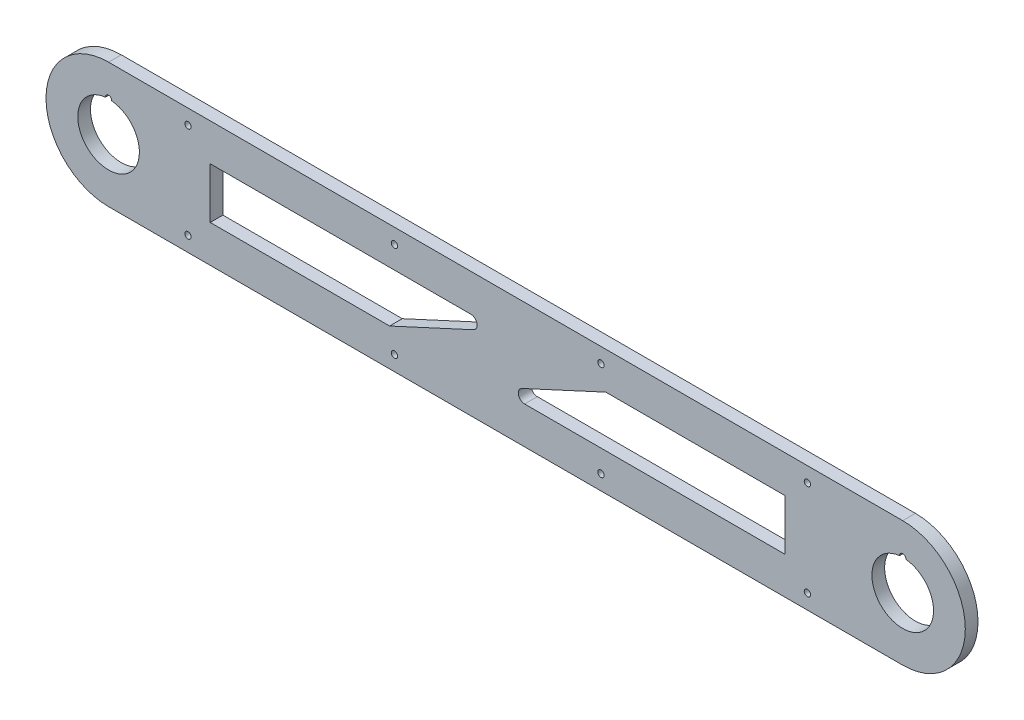
SolidWorks part; units mm, degrees
ref_plane "前视基准面" through (0, 0, 0) normal (0, 0, 1) x (1, 0, 0)
ref_plane "上视基准面" through (0, 0, 0) normal (0, 1, 0) x (1, 0, 0)
ref_plane "右视基准面" through (0, 0, 0) normal (1, 0, 0) x (0, 0, -1)
sketch "草图1" plane through (0, 0, 0) normal (0, 0, 1) x (1, 0, 0)
  line L0 (0, 0) -> (250, 0) construction
  line L1 (0, 0) -> (0, 15.4343) construction
  line L6 (0, 0) -> (0, -15.4343) construction
  line L7 (0, 19.7) -> (250, 19.7)
  line L8 (0, -19.7) -> (250, -19.7)
  line L9 (250, 0) -> (225.3628, 42.6729) construction
  line L10 (240.15, 17.0607) -> (232.3558, 12.5607) construction
  line L11 (0, 19.7) -> (232.3558, 12.5607) construction
  line L12 (240.15, -17.0607) -> (232.3558, -12.5607) construction
  line L13 (0, -19.7) -> (232.3558, -12.5607) construction
  circle A0 centre (0, 0) radius 9.7
  circle A1 centre (250, 0) radius 9.7
  circle A2 centre (0, 0) radius 19.7 construction
  circle A3 centre (250, 0) radius 19.7 construction
  arc A4 (0, 19.7) -> (0, -19.7) centre (0, 0) ccw
  arc A7 (240.15, -17.0607) -> (250, 19.7) centre (250, 0) ccw construction
  arc A8 (250, 19.7) -> (250, -19.7) centre (250, 0) cw
  dimension "D1" = 10
  dimension "D2" = 19.4
  dimension "D3" = 60
extrude "凸台-拉伸1" add sketch "草图1" along normal blind 4
sketch "草图2" plane through (0, 0, 4) normal (0, 0, 1) x (1, 0, 0)
  line L0 (0, 0) -> (250, 0) construction
  line L1 (0, 0) -> (0, -8.921) construction
  circle A0 centre (25, 15) radius 1
  circle A1 centre (90, 15) radius 1
  circle A2 centre (155, 15) radius 1
  circle A3 centre (220, 15) radius 1
  circle A4 centre (90, -15) radius 1
  circle A5 centre (155, -15) radius 1
  circle A6 centre (220, -15) radius 1
  circle A7 centre (25, -15) radius 1
  dimension "D1" = 2
  dimension "D2" = 25
  dimension "D3" = 15
extrude "切除-拉伸1" cut sketch "草图2" against normal blind 10
sketch "草图3" plane through (0, 0, 4) normal (0, 0, 1) x (1, 0, 0)
  line L4 (32, 8) -> (114.0233, 8)
  line L5 (114.8614, 4.1841) -> (88.4625, -8)
  line L6 (88.4625, -8) -> (32, -8)
  line L7 (32, -8) -> (32, 8)
  line L13 (156.5375, 8) -> (130.1386, -4.1841)
  line L14 (213, -8) -> (130.9767, -8)
  line L15 (213, 8) -> (213, -8)
  line L16 (156.5375, 8) -> (213, 8)
  arc A0 (130.9767, -8) -> (130.1386, -4.1841) centre (130.9767, -6) cw
  arc A1 (114.8614, 4.1841) -> (114.0233, 8) centre (114.0233, 6) ccw
  dimension "D1" = 2
extrude "切除-拉伸2" cut sketch "草图3" against normal blind 10
sketch "草图4" plane through (0, 0, 4) normal (0, 0, 1) x (1, 0, 0)
  circle A0 centre (0, 9.7) radius 1
  circle A1 centre (0, 0) radius 9.7 construction
  circle A2 centre (250, 9.7) radius 1
  circle A3 centre (250, 0) radius 9.7 construction
extrude "切除-拉伸3" cut sketch "草图4" against normal blind 10
